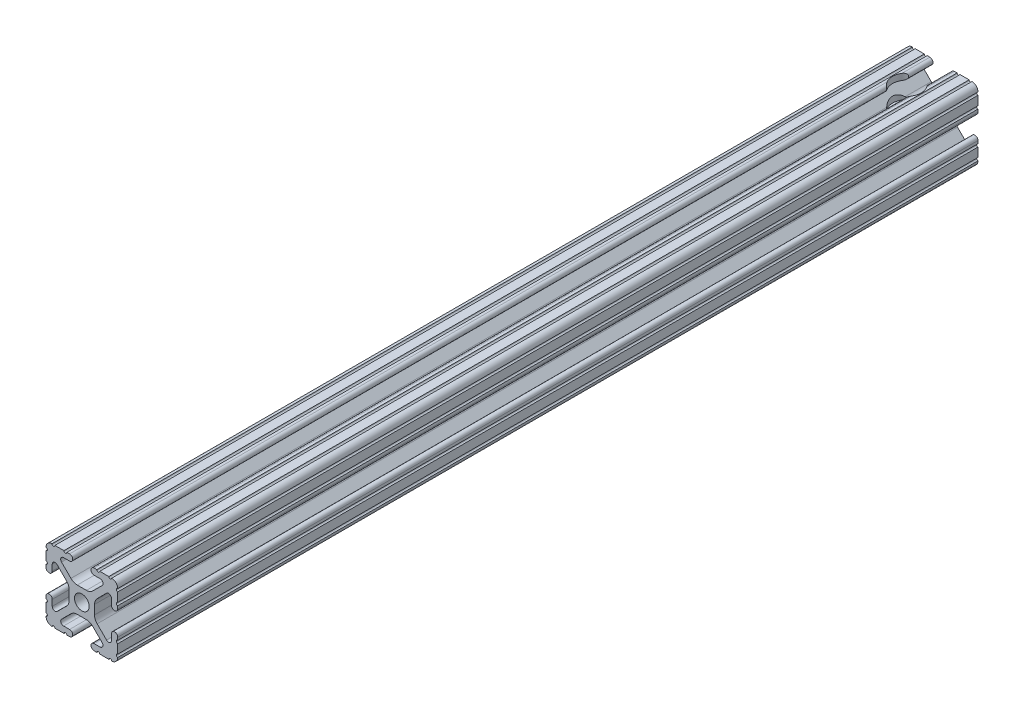
SolidWorks part; units mm, degrees
ref_plane "Front Plane" through (0, 0, 0) normal (0, 0, 1) x (1, 0, 0)
ref_plane "Top Plane" through (0, 0, 0) normal (0, 1, 0) x (1, 0, 0)
ref_plane "Right Plane" through (0, 0, 0) normal (1, 0, 0) x (0, 0, -1)
ref_plane "Plane1" through (0, 0, -25.4) normal (0, 0, -1) x (-1, 0, 0)
sketch "Sketch1" plane through (0, 0, -25.4) normal (0, 0, -1) x (-1, 0, 0)
  line L0 (12.7, -9.5504) -> (12.7, -6.3331)
  line L1 (12.7, -5.3171) -> (12.7, -4.3434)
  line L2 (10.4902, -4.3434) -> (10.4902, -6.4748)
  line L3 (8.7558, -7.1932) -> (5.4257, -3.8632)
  line L4 (4.4958, -1.6181) -> (4.4958, 1.6181)
  line L5 (5.4257, 3.8632) -> (8.7558, 7.1932)
  line L6 (10.4902, 6.4748) -> (10.4902, 4.3434)
  line L7 (12.7, 4.3434) -> (12.7, 5.3171)
  line L8 (12.7, 6.3331) -> (12.7, 9.5504)
  line L9 (9.5504, 12.7) -> (6.3331, 12.7)
  line L10 (5.3171, 12.7) -> (4.3434, 12.7)
  line L11 (4.3434, 10.4902) -> (6.4748, 10.4902)
  line L12 (7.1932, 8.7558) -> (3.8632, 5.4257)
  line L13 (1.6181, 4.4958) -> (-1.6181, 4.4958)
  line L14 (-3.8632, 5.4257) -> (-7.1932, 8.7558)
  line L15 (-6.4748, 10.4902) -> (-4.3434, 10.4902)
  line L16 (-4.3434, 12.7) -> (-5.3171, 12.7)
  line L17 (-6.3331, 12.7) -> (-9.5504, 12.7)
  line L18 (-12.7, 9.5504) -> (-12.7, 6.3331)
  line L19 (-12.7, 5.3171) -> (-12.7, 4.3434)
  line L20 (-10.4902, 4.3434) -> (-10.4902, 6.4748)
  line L21 (-8.7558, 7.1932) -> (-5.4257, 3.8632)
  line L22 (-4.4958, 1.6181) -> (-4.4958, -1.6181)
  line L23 (-5.4257, -3.8632) -> (-8.7558, -7.1932)
  line L24 (-10.4902, -6.4748) -> (-10.4902, -4.3434)
  line L25 (-12.7, -4.3434) -> (-12.7, -5.3171)
  line L26 (-12.7, -6.3331) -> (-12.7, -9.5504)
  line L27 (-9.5504, -12.7) -> (-6.3331, -12.7)
  line L28 (-5.3171, -12.7) -> (-4.3434, -12.7)
  line L29 (-4.3434, -10.4902) -> (-6.4748, -10.4902)
  line L30 (-7.1932, -8.7558) -> (-3.8632, -5.4257)
  line L31 (-1.6181, -4.4958) -> (1.6181, -4.4958)
  line L32 (3.8632, -5.4257) -> (7.1932, -8.7558)
  line L33 (6.4748, -10.4902) -> (4.3434, -10.4902)
  line L34 (4.3434, -12.7) -> (5.3171, -12.7)
  line L35 (6.3331, -12.7) -> (9.5504, -12.7)
  arc A0 (12.6998, -10.5664) -> (12.7, -9.5504) centre (12.7, -10.0584) cw
  arc A1 (12.7, -6.3331) -> (12.7, -5.3171) centre (12.7, -5.8251) cw
  arc A2 (12.7, -4.3434) -> (10.4902, -4.3434) centre (11.5951, -4.3434) ccw
  arc A3 (10.4902, -6.4748) -> (8.7558, -7.1932) centre (9.4742, -6.4748) cw
  arc A4 (5.4257, -3.8632) -> (4.4958, -1.6181) centre (7.6708, -1.6181) cw
  arc A5 (4.4958, 1.6181) -> (5.4257, 3.8632) centre (7.6708, 1.6181) cw
  arc A6 (8.7558, 7.1932) -> (10.4902, 6.4748) centre (9.4742, 6.4748) cw
  arc A7 (10.4902, 4.3434) -> (12.7, 4.3434) centre (11.5951, 4.3434) ccw
  arc A8 (12.7, 5.3171) -> (12.7, 6.3331) centre (12.7, 5.8251) cw
  arc A9 (12.7, 9.5504) -> (12.6998, 10.5664) centre (12.7, 10.0584) cw
  arc A10 (12.6998, 10.5664) -> (10.5664, 12.6998) centre (10.5918, 10.5918) ccw
  arc A11 (10.5664, 12.6998) -> (9.5504, 12.7) centre (10.0584, 12.7) cw
  arc A12 (6.3331, 12.7) -> (5.3171, 12.7) centre (5.8251, 12.7) cw
  arc A13 (4.3434, 12.7) -> (4.3434, 10.4902) centre (4.3434, 11.5951) ccw
  arc A14 (6.4748, 10.4902) -> (7.1932, 8.7558) centre (6.4748, 9.4742) cw
  arc A15 (3.8632, 5.4257) -> (1.6181, 4.4958) centre (1.6181, 7.6708) cw
  arc A16 (-1.6181, 4.4958) -> (-3.8632, 5.4257) centre (-1.6181, 7.6708) cw
  arc A17 (-7.1932, 8.7558) -> (-6.4748, 10.4902) centre (-6.4748, 9.4742) cw
  arc A18 (-4.3434, 10.4902) -> (-4.3434, 12.7) centre (-4.3434, 11.5951) ccw
  arc A19 (-5.3171, 12.7) -> (-6.3331, 12.7) centre (-5.8251, 12.7) cw
  arc A20 (-9.5504, 12.7) -> (-10.5664, 12.6998) centre (-10.0584, 12.7) cw
  arc A21 (-10.5664, 12.6998) -> (-12.6998, 10.5664) centre (-10.5918, 10.5918) ccw
  arc A22 (-12.6998, 10.5664) -> (-12.7, 9.5504) centre (-12.7, 10.0584) cw
  arc A23 (-12.7, 6.3331) -> (-12.7, 5.3171) centre (-12.7, 5.8251) cw
  arc A24 (-12.7, 4.3434) -> (-10.4902, 4.3434) centre (-11.5951, 4.3434) ccw
  arc A25 (-10.4902, 6.4748) -> (-8.7558, 7.1932) centre (-9.4742, 6.4748) cw
  arc A26 (-5.4257, 3.8632) -> (-4.4958, 1.6181) centre (-7.6708, 1.6181) cw
  arc A27 (-4.4958, -1.6181) -> (-5.4257, -3.8632) centre (-7.6708, -1.6181) cw
  arc A28 (-8.7558, -7.1932) -> (-10.4902, -6.4748) centre (-9.4742, -6.4748) cw
  arc A29 (-10.4902, -4.3434) -> (-12.7, -4.3434) centre (-11.5951, -4.3434) ccw
  arc A30 (-12.7, -5.3171) -> (-12.7, -6.3331) centre (-12.7, -5.8251) cw
  arc A31 (-12.7, -9.5504) -> (-12.6998, -10.5664) centre (-12.7, -10.0584) cw
  arc A32 (-12.6998, -10.5664) -> (-10.5664, -12.6998) centre (-10.5918, -10.5918) ccw
  arc A33 (-10.5664, -12.6998) -> (-9.5504, -12.7) centre (-10.0584, -12.7) cw
  arc A34 (-6.3331, -12.7) -> (-5.3171, -12.7) centre (-5.8251, -12.7) cw
  arc A35 (-4.3434, -12.7) -> (-4.3434, -10.4902) centre (-4.3434, -11.5951) ccw
  arc A36 (-6.4748, -10.4902) -> (-7.1932, -8.7558) centre (-6.4748, -9.4742) cw
  arc A37 (-3.8632, -5.4257) -> (-1.6181, -4.4958) centre (-1.6181, -7.6708) cw
  arc A38 (1.6181, -4.4958) -> (3.8632, -5.4257) centre (1.6181, -7.6708) cw
  arc A39 (7.1932, -8.7558) -> (6.4748, -10.4902) centre (6.4748, -9.4742) cw
  arc A40 (4.3434, -10.4902) -> (4.3434, -12.7) centre (4.3434, -11.5951) ccw
  arc A41 (5.3171, -12.7) -> (6.3331, -12.7) centre (5.8251, -12.7) cw
  arc A42 (9.5504, -12.7) -> (10.5664, -12.6998) centre (10.0584, -12.7) cw
  arc A43 (10.5664, -12.6998) -> (12.6998, -10.5664) centre (10.5918, -10.5918) ccw
  circle A44 centre (0, 0) radius 2.6035
extrude "Boss-Extrude1" add sketch "Sketch1" along normal blind 304.8
sketch "Sketch2" plane through (0, 12.7, 0) normal (0, 1, 0) x (1, 0, 0)
  circle A0 centre (0, 317.6785) radius 3.81
  dimension "D1" = 7.62
extrude "Cut-Extrude1" cut sketch "Sketch2" against normal up to surface (25.4 mm away) up to face at (-7.9417, -12.7, -177.8)
sketch "Sketch3" plane through (0, 12.7, 0) normal (0, 1, 0) x (1, 0, 0)
  circle A0 centre (0, 317.6785) radius 5.08
  dimension "D1" = 10.16
extrude "Cut-Extrude2" cut sketch "Sketch3" against normal up to surface (8.2042 mm away) up to face at (0, 4.4958, -325.7541)
